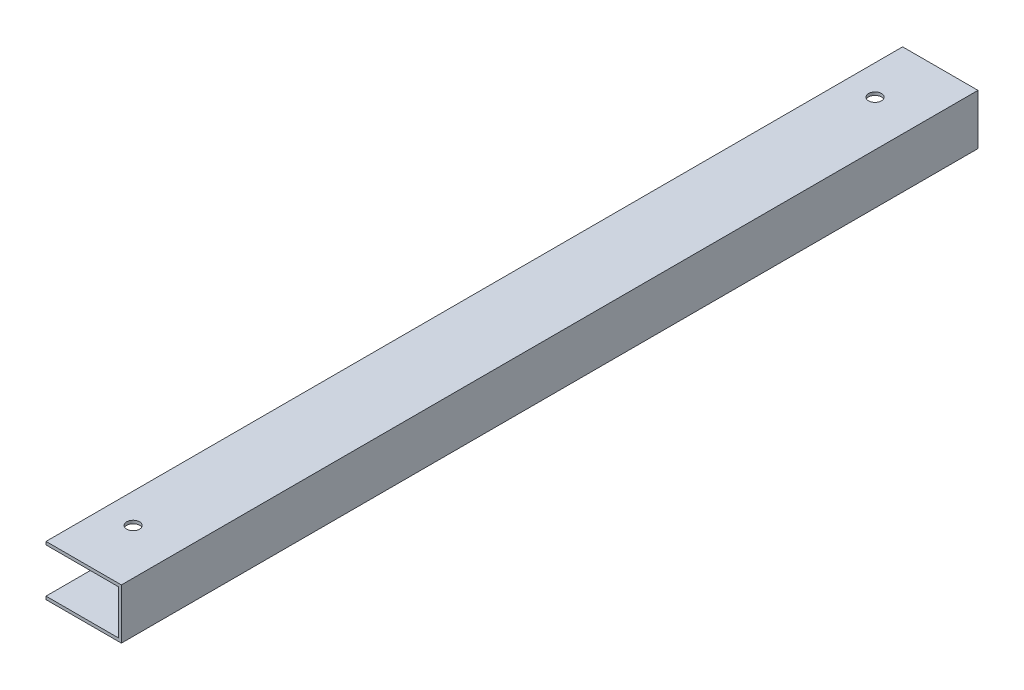
SolidWorks part; units mm, degrees
ref_plane "Alzado" through (0, 0, 0) normal (0, 0, 1) x (1, 0, 0)
ref_plane "Planta" through (0, 0, 0) normal (0, 1, 0) x (1, 0, 0)
ref_plane "Vista lateral" through (0, 0, 0) normal (1, 0, 0) x (0, 0, -1)
sketch "Croquis2" plane through (0, 0, 0) normal (0, 0, 1) x (1, 0, 0)
  line L1 (38.1, -25.5) -> (-38.1, -25.5)
  line L2 (38.1, -25.5) -> (38.1, 25.5)
  line L3 (38.1, 25.5) -> (-38.1, 25.5)
  line L4 (-38.1, -25.5) -> (-38.1, 25.5)
  line L5 (38.1, -25.5) -> (-38.1, 25.5) construction
  line L6 (38.1, 25.5) -> (-38.1, -25.5) construction
  point P0 (0, 0)
  point P6 (0, 25.5)
  dimension "D1" = 51
  dimension "D2" = 76.2
extrude "Saliente-Extruir1" add sketch "Croquis2" along normal mid plane 866
sketch "Croquis6" plane through (0, 0, 433) normal (0, 0, 1) x (1, 0, 0)
  line L4 (-38.1, 25.5) -> (-38.1, -25.5)
  line L5 (-38.1, -25.5) -> (38.1, -25.5)
  line L6 (38.1, -25.5) -> (38.1, 25.5)
  line L7 (38.1, 25.5) -> (-38.1, 25.5)
  line L8 (-38.1, 25.5) -> (-38.1, -25.5)
  line L9 (-38.1, -25.5) -> (38.1, -25.5)
  line L10 (38.1, -25.5) -> (38.1, 25.5)
  line L11 (38.1, 25.5) -> (-38.1, 25.5)
  line L16 (-35, 22.4) -> (-35, -22.4)
  line L17 (-35, -22.4) -> (35, -22.4)
  line L18 (35, -22.4) -> (35, 22.4)
  line L19 (35, 22.4) -> (-35, 22.4)
  line L20 (-35, 22.4) -> (-35, -22.4)
  line L21 (-35, -22.4) -> (35, -22.4)
  line L22 (35, -22.4) -> (35, 22.4)
  line L23 (35, 22.4) -> (-35, 22.4)
  dimension "D1" = 0
  dimension "D2" = 3.1
extrude "Cortar-Extruir1" cut sketch "Croquis6" against normal blind 900 contours L22 L23 L20 L21
sketch "Croquis7" plane through (-38.1, 0, 0) normal (-1, 0, 0) x (0, 0, 1)
  line L0 (-433, 25.5) -> (-433, -25.5) construction
  line L1 (433, -22.4) -> (-433, -22.4)
  line L2 (433, -22.4) -> (433, 22.4)
  line L3 (433, 22.4) -> (-433, 22.4)
  line L4 (-433, -22.4) -> (-433, 22.4)
  line L5 (433, -22.4) -> (-433, 22.4) construction
  line L6 (433, 22.4) -> (-433, -22.4) construction
  line L7 (433, -25.5) -> (-433, -25.5) construction
  point P0 (0, 0)
  dimension "D1" = 3.1
extrude "Cortar-Extruir2" cut sketch "Croquis7" against normal blind 20
sketch "Croquis8" plane through (0, 25.5, 0) normal (0, 1, 0) x (1, 0, 0)
  line L0 (-121.5247, 0) -> (93.3442, 0) construction
  line L1 (0, 497.4221) -> (0, -494.6167) construction
  circle A0 centre (-8, 375) radius 6.5
  circle A1 centre (-8, -375) radius 6.5
  point P7 (0, 0)
  point P10 (-16.3136, 375)
  dimension "D1" = 13
  dimension "D2" = 375
  dimension "D3" = 8
extrude "Cortar-Extruir3" cut sketch "Croquis8" against normal blind 80
